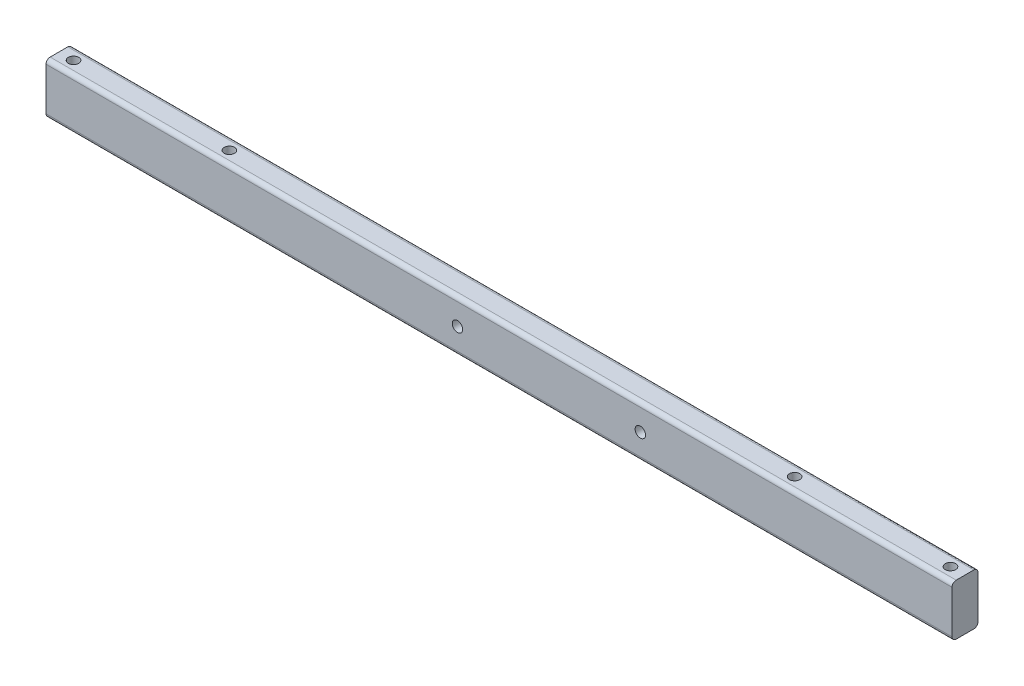
SolidWorks part; units mm, degrees
material "1060 Alloy"
ref_plane "Front Plane" through (0, 0, 0) normal (0, 0, 1) x (1, 0, 0)
ref_plane "Top Plane" through (0, 0, 0) normal (0, 1, 0) x (1, 0, 0)
ref_plane "Right Plane" through (0, 0, 0) normal (1, 0, 0) x (0, 0, -1)
sketch "Sketch1" plane through (0, 0, 0) normal (0, 0, 1) x (1, 0, 0)
  line L0 (-218, 6.15) -> (218, 6.15) construction
  line L1 (0, 0) -> (218, 0)
  line L2 (0, 0) -> (0, 12.3)
  line L3 (0, 12.3) -> (218, 12.3)
  line L4 (218, 0) -> (218, 12.3)
  circle A0 centre (143, 6.15) radius 1.25
  circle A1 centre (99, 6.15) radius 1.25
  point P8 (0, 6.15)
  dimension "D3" = 75
  dimension "D4" = 44
  dimension "D5" = 2.5
  dimension "D6" = 2.5
  dimension "D1" = 218
  dimension "D2" = 12.3
extrude "Boss-Extrude1" add sketch "Sketch1" along normal blind 6.25
sketch "Sketch2" plane through (0, 12.3, 0) normal (0, 1, 0) x (1, 0, 0)
  line L0 (109, 6.25) -> (109, -6.25) construction
  line L2 (218, -6.25) -> (0, -6.25) construction
  line L3 (327, -3.125) -> (109, -3.125) construction
  line L5 (218, -6.25) -> (218, 0) construction
  circle A0 centre (214.5, -3.125) radius 1.25
  circle A1 centre (177, -3.125) radius 1.25
  circle A2 centre (3.5, -3.125) radius 1.25
  circle A3 centre (41, -3.125) radius 1.25
  point P3 (109, 0)
  point P8 (218, -3.125)
  dimension "D1" = 3.5
  dimension "D2" = 2.5
  dimension "D3" = 37.5
  dimension "D4" = 2.5
extrude "Cut-Extrude1" cut sketch "Sketch2" against normal blind 8
fillet "Fillet1" radius 1 4 edges at (109, 12.3, 0) (109, 0, 0) (109, 0, 6.25) (109, 12.3, 6.25)
